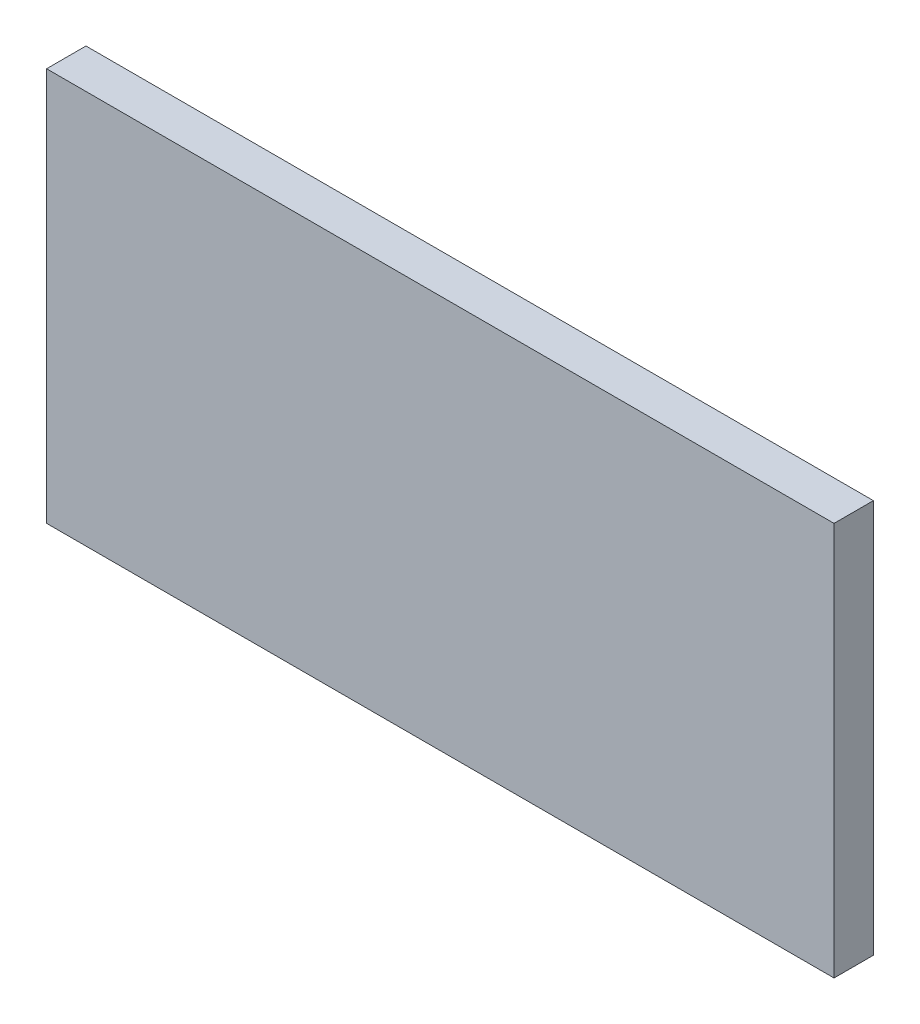
SolidWorks part; units mm, degrees
ref_plane "Front Plane" through (0, 0, 0) normal (0, 0, 1) x (1, 0, 0)
ref_plane "Top Plane" through (0, 0, 0) normal (0, 1, 0) x (1, 0, 0)
ref_plane "Right Plane" through (0, 0, 0) normal (1, 0, 0) x (0, 0, -1)
sketch "Sketch1" plane through (0, 0, 0) normal (0, 0, 1) x (1, 0, 0)
  line L1 (-12.7, -6.35) -> (12.7, -6.35)
  line L2 (-12.7, -6.35) -> (-12.7, 6.35)
  line L3 (-12.7, 6.35) -> (12.7, 6.35)
  line L4 (12.7, -6.35) -> (12.7, 6.35)
  line L5 (-12.7, -6.35) -> (12.7, 6.35) construction
  line L6 (-12.7, 6.35) -> (12.7, -6.35) construction
  point P1 (0, 0)
  dimension "D1" = 25.4
  dimension "D2" = 12.7
extrude "Boss-Extrude1" add sketch "Sketch1" along normal blind 1.27
